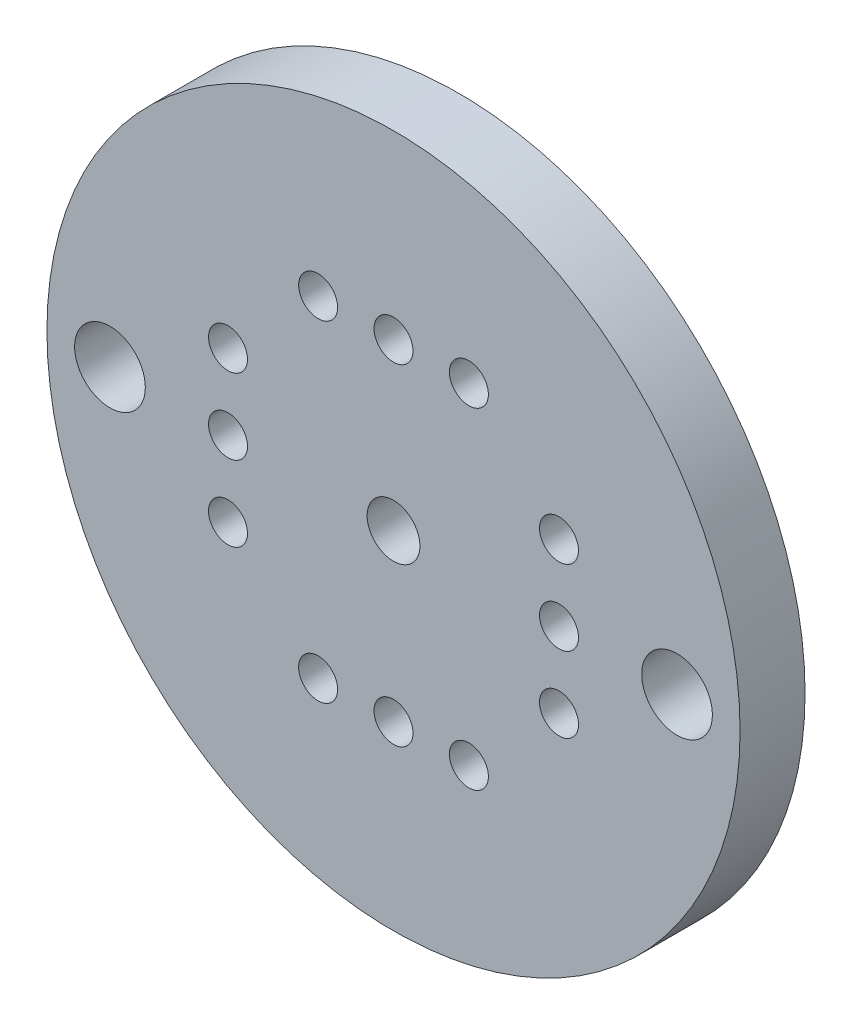
SolidWorks part; units mm, degrees
ref_plane "Front Plane" through (0, 0, 0) normal (0, 0, 1) x (1, 0, 0)
ref_plane "Top Plane" through (0, 0, 0) normal (0, 1, 0) x (1, 0, 0)
ref_plane "Right Plane" through (0, 0, 0) normal (1, 0, 0) x (0, 0, -1)
sketch "Sketch1" plane through (0, 0, 0) normal (0, 0, 1) x (1, 0, 0)
  circle A0 centre (0, 0) radius 16
  dimension "D1" = 32
extrude "Boss-Extrude1" add sketch "Sketch1" along normal blind 3
hole_wizard "M1.6 Clearance Hole1" positions "Sketch2" profile "Sketch3" hole size "M1.6" standard "ANSI Metric" end condition through all
sketch "Sketch2" plane through (0, 0, 3) normal (0, 0, 1) x (1, 0, 0)
  circle A0 centre (0, 0) radius 10.175 construction
  point P0 (-3.48, 7.64)
  point P2 (0, 7.64)
  point P3 (3.48, 7.64)
  point P5 (7.64, 3.48)
  point P7 (7.64, -3.48)
  point P9 (7.64, 0)
  point P11 (3.48, -7.64)
  point P13 (0, -7.64)
  point P15 (-3.48, -7.64)
  point P17 (-7.64, 0)
  point P19 (-7.64, -3.48)
  point P21 (-7.64, 3.48)
  point P40 (0, 0)
  point P42 (0, 0)
  point P43 (0, 0)
  point P44 (0, 0)
  point P45 (0, 0)
  dimension "D1" = 20.35
  dimension "D2" = 7.64
  dimension "D3" = 7.64
  dimension "D4" = 7.64
  dimension "D5" = 7.64
  dimension "D6" = 3.48
  dimension "D7" = 3.48
  dimension "D8" = 3.48
  dimension "D9" = 3.48
sketch "Sketch3" plane through (-3.48, 7.64, 3) normal (1, 0, 0) x (0, -1, 0)
  line L0 (0, 0) -> (0, 3)
  line L1 (0, 3) -> (0.9, 3)
  line L2 (0.9, 3) -> (0.9, 0)
  line L5 (0.9, 0) -> (0, 0)
  line L11 (0, -6.35) -> (0, 107.95) construction
  dimension "Thru Hole Dia." = 1.8
  dimension "Thru Hole Depth" = 3
hole_wizard "#4 Clearance Hole1" positions "Sketch4" profile "Sketch5" hole size "#4" standard "ANSI Inch" end condition through all
sketch "Sketch4" plane through (0, 0, 3) normal (0, 0, 1) x (1, 0, 0)
  point P0 (-13.09, 0)
  point P2 (13.09, 0)
  dimension "D1" = 26.18
  dimension "D2" = 13.09
sketch "Sketch5" plane through (-13.09, 0, 3) normal (1, 0, 0) x (0, -1, 0)
  line L0 (0, 0) -> (0, 3)
  line L1 (0, 3) -> (1.6319, 3)
  line L2 (1.6319, 3) -> (1.632, 0)
  line L5 (1.632, 0) -> (0, 0)
  line L11 (0, -6.35) -> (0, 107.95) construction
  dimension "Thru Hole Dia." = 3.2639
  dimension "Thru Hole Depth" = 3
hole_wizard "#2 Clearance Hole1" positions "Sketch7" profile "Sketch8" hole size "#2" standard "ANSI Inch" end condition through all
sketch "Sketch7" plane through (0, 0, 3) normal (0, 0, 1) x (1, 0, 0)
  point P0 (0, 0)
sketch "Sketch8" plane through (0, 0, 3) normal (1, 0, 0) x (0, -1, 0)
  line L0 (0, 0) -> (0, 3)
  line L1 (0, 3) -> (1.2192, 3)
  line L2 (1.2192, 3) -> (1.2192, 0)
  line L5 (1.2192, 0) -> (0, 0)
  line L11 (0, -6.35) -> (0, 107.95) construction
  dimension "Thru Hole Dia." = 2.4384
  dimension "Thru Hole Depth" = 3
equation "\"D3@Sketch2\"=\"D2@Sketch2\""
equation "\"D4@Sketch2\"=\"D2@Sketch2\""
equation "\"D5@Sketch2\"=\"D2@Sketch2\""
equation "\"D7@Sketch2\"=\"D6@Sketch2\""
equation "\"D9@Sketch2\"=\"D8@Sketch2\""
equation "\"D2@Sketch4\"=\"D1@Sketch4\"/2"
